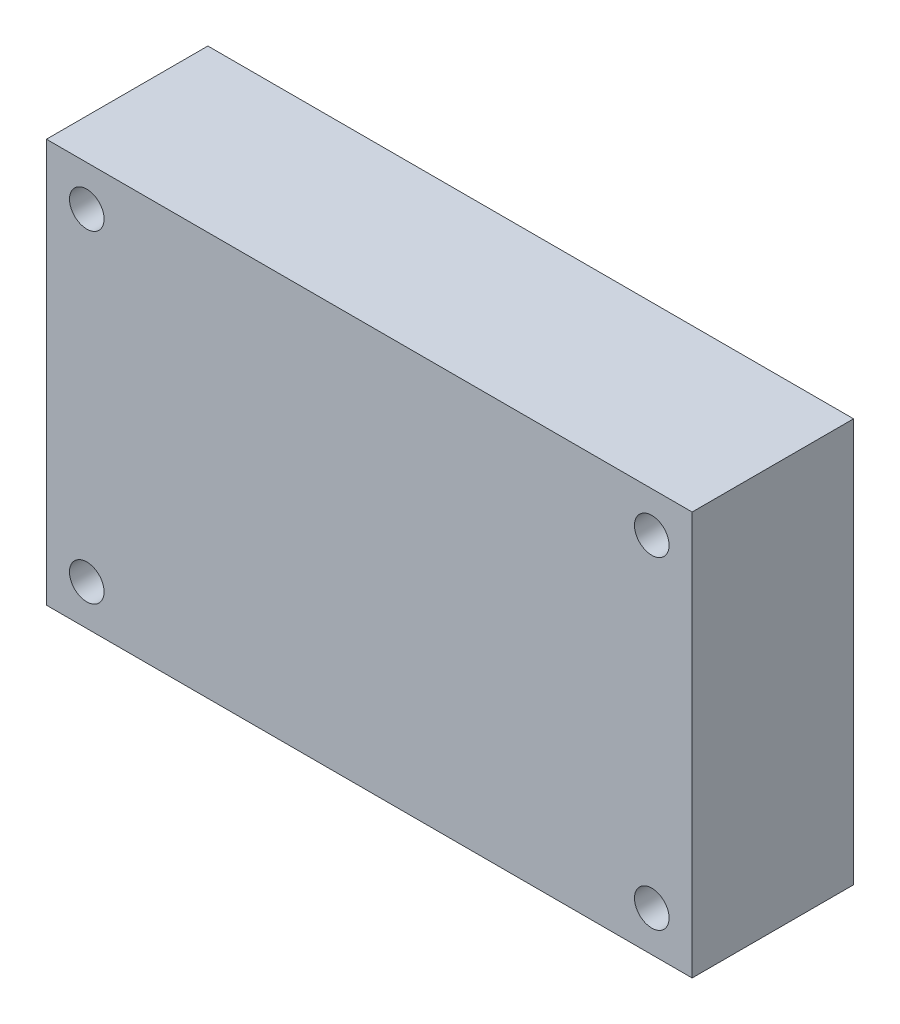
SolidWorks part; units mm, degrees
ref_plane "Front" through (0, 0, 0) normal (0, 0, 1) x (1, 0, 0)
ref_plane "Top" through (0, 0, 0) normal (0, 1, 0) x (1, 0, 0)
ref_plane "Right" through (0, 0, 0) normal (1, 0, 0) x (0, 0, -1)
sketch "Sketch1" plane through (0, 0, 0) normal (0, 0, 1) x (1, 0, 0)
  line L1 (0, 0) -> (56, 0)
  line L2 (0, 0) -> (0, 35)
  line L3 (0, 35) -> (56, 35)
  line L4 (56, 0) -> (56, 35)
  dimension "D1" = 56
  dimension "D2" = 35
extrude "Boss-Extrude1" add sketch "Sketch1" along normal blind 14
sketch "Sketch2" plane through (0, 0, 14) normal (0, 0, 1) x (1, 0, 0)
  line L0 (56, 35) -> (0, 35) construction
  line L1 (0, 35) -> (0, 0) construction
  line L2 (56, 0) -> (56, 35) construction
  line L3 (0, 0) -> (56, 0) construction
  circle A0 centre (3.5, 31.5) radius 1.5
  circle A1 centre (3.5, 3.5) radius 1.5
  circle A2 centre (52.5, 31.5) radius 1.5
  circle A3 centre (52.5, 3.5) radius 1.5
  dimension "D9" = 3
  dimension "D10" = 3
  dimension "D11" = 3
  dimension "D12" = 3
  dimension "D1" = 3.5
  dimension "D2" = 3.5
  dimension "D3" = 3.5
  dimension "D4" = 3.5
  dimension "D5" = 3.5
  dimension "D6" = 3.5
  dimension "D7" = 3.5
  dimension "D8" = 3.5
extrude "Cut-Extrude1" cut sketch "Sketch2" against normal blind 10
